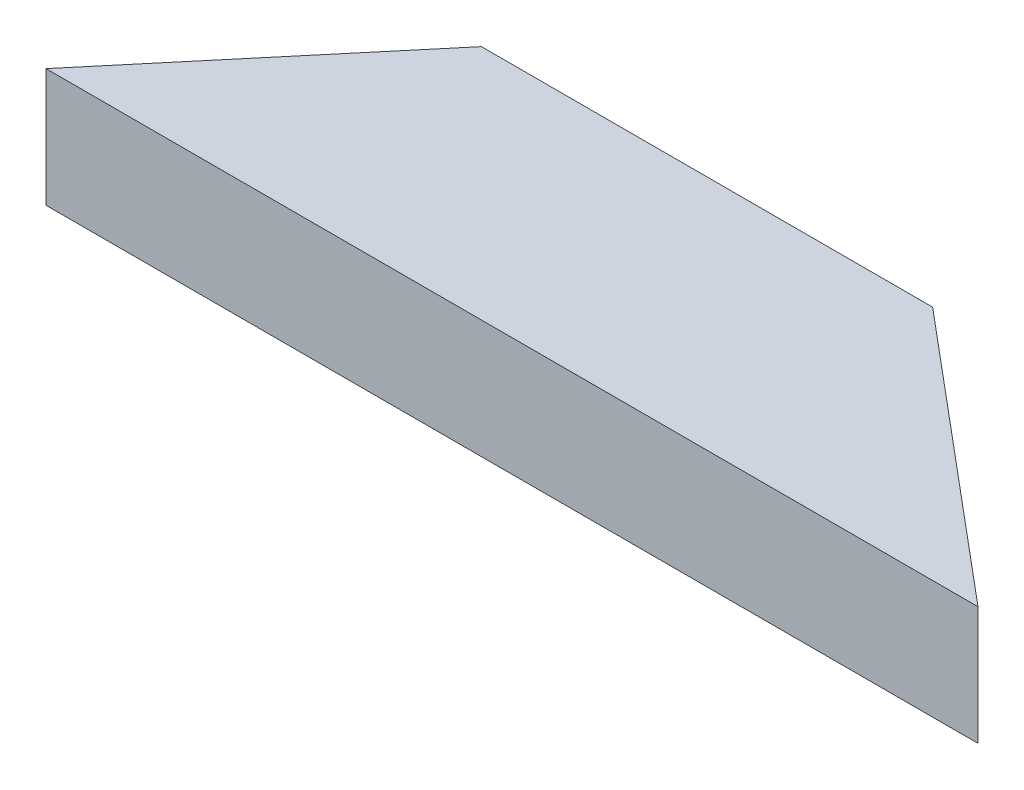
SolidWorks part; units mm, degrees
material "Pine"
ref_plane "Front Plane" through (0, 0, 0) normal (0, 0, 1) x (1, 0, 0)
ref_plane "Top Plane" through (0, 0, 0) normal (0, 1, 0) x (1, 0, 0)
ref_plane "Right Plane" through (0, 0, 0) normal (1, 0, 0) x (0, 0, -1)
sketch "Sketch1" plane through (0, 0, 0) normal (0, 1, 0) x (1, 0, 0)
  line L0 (0, 0) -> (400, 0)
  line L1 (400, 0) -> (278.933, 101.6)
  line L2 (278.933, 101.6) -> (85.2632, 101.6)
  line L3 (85.2632, 101.6) -> (0, 0)
  line L4 (200, 0) -> (200, 101.6) construction
  line L5 (0, 0) -> (165.2946, 196.9658) construction
  line L6 (165.2946, 196.9658) -> (400, 0) construction
  dimension "D1" = 101.6
  dimension "D2" = 400
  dimension "D3" = 193.6698
extrude "Boss-Extrude1" add sketch "Sketch1" along normal blind 50.8
